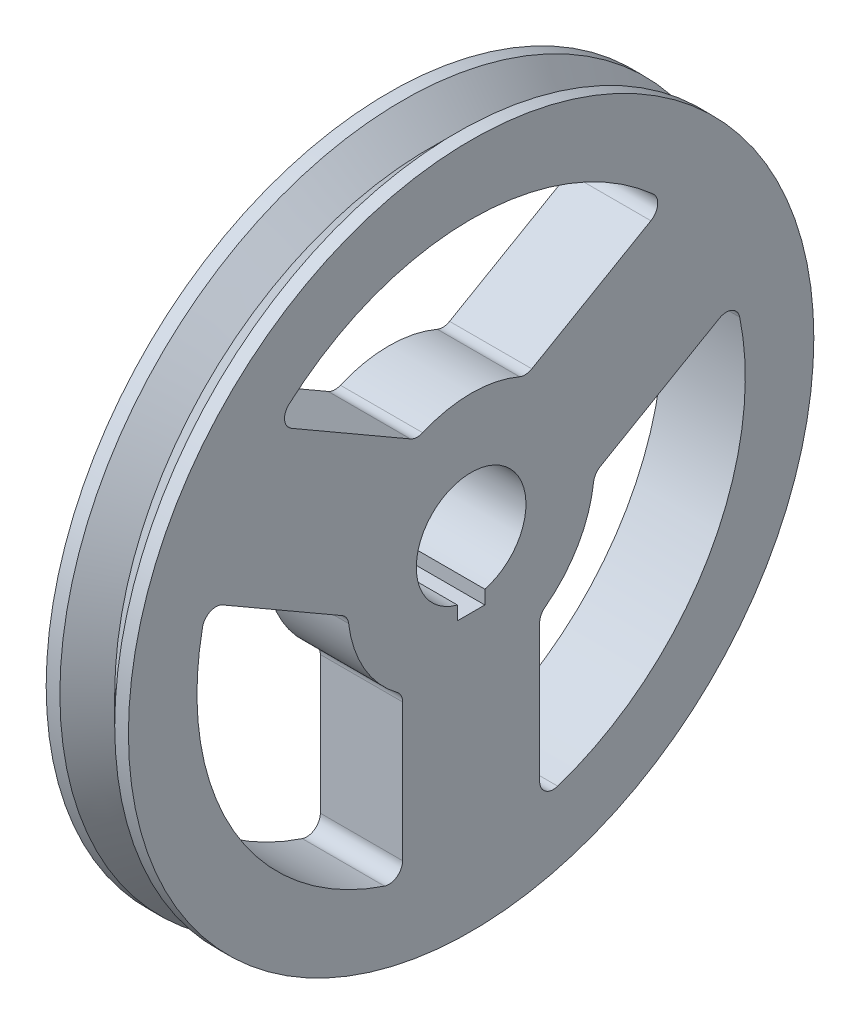
SolidWorks part; units mm, degrees
other "Markup2"
sketch "Sketch6" plane through (-15, 125, -125) normal (-0.9855, 0.1694, -0.0055) x (0.0981, 0.597, 0.7963)
ref_plane "Front Plane" through (0, 0, 0) normal (0, 0, 1) x (1, 0, 0)
ref_plane "Top Plane" through (0, 0, 0) normal (0, 1, 0) x (1, 0, 0)
ref_plane "Right Plane" through (0, 0, 0) normal (1, 0, 0) x (0, 0, -1)
sketch "Sketch1" plane through (0, 0, 0) normal (0, 1, 0) x (1, 0, 0)
  line L0 (0, 0) -> (37.2314, 0) construction
  line L5 (-15, 125) -> (-15, 100)
  line L6 (-15, 100) -> (15, 100)
  line L7 (15, 100) -> (15, 125)
  line L8 (15, 125) -> (10, 125)
  line L9 (10, 125) -> (0, 115)
  line L10 (0, 115) -> (-10, 125)
  line L11 (-10, 125) -> (-15, 125)
  line L12 (15, 100) -> (15, 0) construction
  line L13 (-15, 100) -> (-15, 0) construction
  line L14 (-15, 0) -> (0, 0) construction
  line L15 (-15, 45) -> (15, 45)
  line L16 (-15, 20) -> (15, 20)
  line L17 (15, 20) -> (15, 45)
  line L18 (-15, 20) -> (-15, 45)
  line L19 (15, 0) -> (15, 20)
  line L20 (-15, 0) -> (-15, 20)
  point P12 (0, 100)
  point P25 (15, 45)
  point P29 (-15, 45)
  dimension "D1" = 30
  dimension "D2" = 100
  dimension "D3" = 125
  dimension "D4" = 5
  dimension "D5" = 10
  dimension "D7" = 45
  dimension "D8" = 20
revolve "Revolve1" add sketch "Sketch1" angle 360 mid plane about L0
sketch "Sketch2" plane through (0, 0, 0) normal (1, 0, 0) x (0, 0, -1)
  line L0 (0, 0) -> (0, 125) construction
  line L1 (25, -40) -> (25, -90.1388)
  line L2 (-25, -40) -> (-25, -90.1388)
  line L3 (-47.141, -1.6506) -> (-90.5625, 23.4188)
  line L4 (-22.141, 41.6506) -> (-65.5625, 66.72)
  line L5 (22.141, 41.6506) -> (65.5625, 66.72)
  line L6 (47.141, -1.6506) -> (90.5625, 23.4188)
  circle A0 centre (0, 0) radius 125 construction
  arc A2 (-27, -36) -> (-25, -40) centre (-30, -40) cw
  circle A3 centre (0, 0) radius 100 construction
  circle A4 centre (0, 0) radius 125
  arc A7 (25, -90.1388) -> (31.5789, -94.8829) centre (30, -90.1388) ccw
  arc A8 (-25, -90.1388) -> (-31.5789, -94.8829) centre (-30, -90.1388) cw
  arc A9 (-17.6769, 41.3827) -> (-22.141, 41.6506) centre (-19.641, 45.9808) cw
  arc A10 (-44.6769, -5.3827) -> (-47.141, -1.6506) centre (-49.641, -5.9808) ccw
  arc A11 (-65.5625, 66.72) -> (-66.3816, 74.7896) centre (-63.0625, 71.0502) cw
  arc A12 (-90.5625, 23.4188) -> (-97.9605, 20.0933) centre (-93.0625, 19.0886) ccw
  arc A13 (44.6769, -5.3827) -> (47.141, -1.6506) centre (49.641, -5.9808) cw
  arc A14 (17.6769, 41.3827) -> (22.141, 41.6506) centre (19.641, 45.9808) ccw
  arc A15 (90.5625, 23.4188) -> (97.9605, 20.0933) centre (93.0625, 19.0886) cw
  arc A16 (65.5625, 66.72) -> (66.3816, 74.7896) centre (63.0625, 71.0502) ccw
  arc A17 (97.9605, 20.0933) -> (66.3816, 74.7896) centre (0, 0) ccw
  arc A18 (-31.5789, -94.8829) -> (31.5789, -94.8829) centre (0, 0) ccw
  arc A19 (-17.6769, 41.3827) -> (-44.6769, -5.3827) centre (0, 0) ccw
  arc A20 (-27, -36) -> (27, -36) centre (0, 0) ccw
  arc A21 (17.6769, 41.3827) -> (45, 0) centre (0, 0) cw
  circle A22 centre (0, 0) radius 45 construction
  arc A23 (27, -36) -> (25, -40) centre (30, -40) ccw
  arc A24 (-97.9605, 20.0933) -> (-66.3816, 74.7896) centre (0, 0) cw
  circle A25 centre (0, 0) radius 45
  circle A26 centre (0, 0) radius 45
  circle A27 centre (0, 0) radius 125
  circle A28 centre (0, 0) radius 100
  point P49 (0, 0)
  dimension "D2" = 0
  dimension "D3" = 10
  dimension "D6" = 5
  dimension "D1" = 50
  dimension "D5" = 45
  dimension "D7" = 0
  dimension "D4" = 3
extrude "Boss-Extrude1" add sketch "Sketch2" along normal mid plane 30
sketch "Sketch4" plane through (-15, 0, 0) normal (-1, 0, 0) x (0, 0, 1)
  line L0 (0, 0) -> (0, 125) construction
  line L1 (5, -19.3649) -> (5, -24.3649)
  line L2 (5, -24.3649) -> (-5, -24.3649)
  line L3 (-5, -19.3649) -> (-5, -24.3649)
  circle A0 centre (0, 0) radius 125 construction
  circle A1 centre (0, 0) radius 20 construction
  arc A2 (-5, -19.3649) -> (5, -19.3649) centre (0, 0) ccw
  point P11 (0, -24.3649)
  circle M30 centre (0, 0) radius 20
  dimension "D1" = 5
  dimension "D2" = 5
extrude "Cut-Extrude1" cut sketch "Sketch4" against normal through all contours L3 L2 L1 M30
